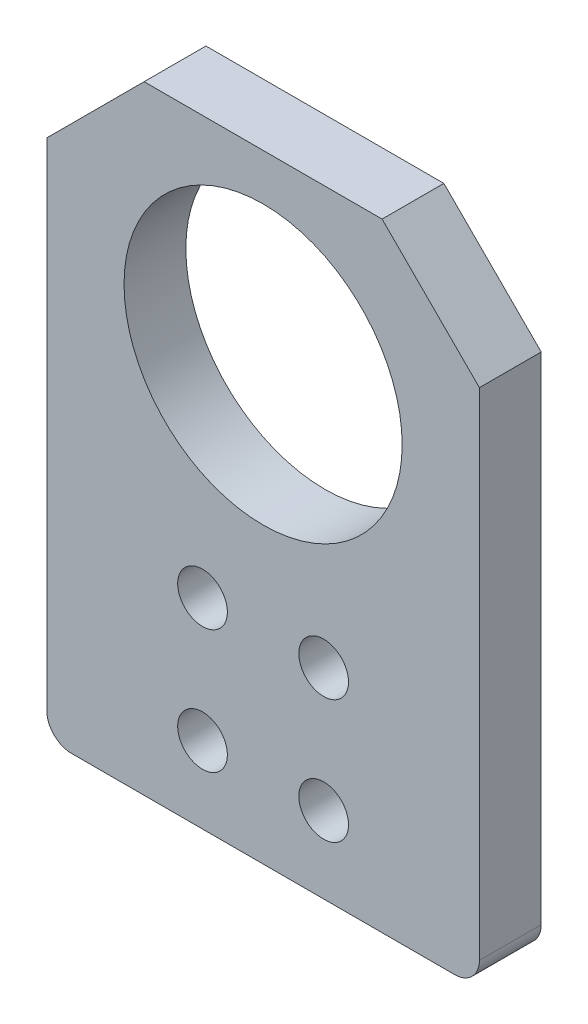
SolidWorks part; units mm, degrees
ref_plane "Front Plane" through (0, 0, 0) normal (0, 0, 1) x (1, 0, 0)
ref_plane "Top Plane" through (0, 0, 0) normal (0, 1, 0) x (1, 0, 0)
ref_plane "Right Plane" through (0, 0, 0) normal (1, 0, 0) x (0, 0, -1)
sketch "Sketch1" plane through (0, 0, 0) normal (0, 0, 1) x (1, 0, 0)
  line L1 (-22.225, -31.75) -> (22.225, -31.75)
  line L2 (-22.225, -31.75) -> (-22.225, 31.75)
  line L3 (-22.225, 31.75) -> (22.225, 31.75)
  line L4 (22.225, -31.75) -> (22.225, 31.75)
  line L5 (-22.225, -31.75) -> (22.225, 31.75) construction
  line L6 (-22.225, 31.75) -> (22.225, -31.75) construction
  point P0 (0, 0)
  dimension "D1" = 44.45
  dimension "D2" = 63.5
extrude "Boss-Extrude1" add sketch "Sketch1" along normal mid plane 6.35
chamfer "Chamfer1" distance 10 angle 45 2 edges at (22.225, 31.75, 0) (-22.225, 31.75, 0)
sketch "Sketch2" plane through (0, 0, 3.175) normal (0, 0, 1) x (1, 0, 0)
  line L0 (12.225, 31.75) -> (-12.225, 31.75) construction
  circle A0 centre (0, 12.7) radius 14.2875
  point P2 (0, 0)
  dimension "D1" = 28.575
  dimension "D2" = 19.05
extrude "Cut-Extrude1" cut sketch "Sketch2" against normal through all
hole_wizard "Tap Drill for #10-24 Tap1" positions "Sketch4" profile "Sketch5" hole size "#10-24" standard "ANSI Inch"
sketch "Sketch4" plane through (0, -31.75, 0) normal (0, -1, 0) x (-1, 0, 0)
  line L0 (15.875, 0) -> (-15.875, 0) construction
  point P0 (15.875, 0)
  point P2 (-15.875, 0)
  point P12 (-6.9325, 0)
  point P13 (0, 0)
  dimension "D1" = 31.75
sketch "Sketch5" plane through (-15.875, -31.75, 0) normal (1, 0, 0) x (0, 0, -1)
  line L0 (0, 0) -> (0, 20.1908)
  line L1 (0, 20.1908) -> (1.8986, 19.05)
  line L2 (1.8986, 19.05) -> (1.8986, 0)
  line L5 (1.8986, 0) -> (0, 0)
  line L10 (0, 20.1908) -> (-1.8987, 19.05) construction
  line L11 (0, -6.35) -> (0, 107.95) construction
  dimension "Hole Dia." = 3.7973
  dimension "Hole Depth" = 19.05
  dimension "Drill Angle" = 118
sketch "Sketch6" plane through (0, 0, 3.175) normal (0, 0, 1) x (1, 0, 0)
  line L0 (-22.225, -31.75) -> (22.225, -31.75) construction
  line L1 (-6.223, -23.876) -> (6.223, -23.876) construction
  line L2 (-6.223, -23.876) -> (-6.223, -11.176) construction
  line L3 (-6.223, -11.176) -> (6.223, -11.176) construction
  line L4 (6.223, -23.876) -> (6.223, -11.176) construction
  line L5 (-6.223, -23.876) -> (6.223, -11.176) construction
  line L6 (-6.223, -11.176) -> (6.223, -23.876) construction
  point P0 (0, -17.526)
  point P5 (0, 0)
  dimension "D1" = 7.874
  dimension "D2" = 12.446
  dimension "D3" = 12.7
hole_wizard "#10 Clearance Hole1" positions "Sketch7" profile "Sketch8" hole size "#10" standard "ANSI Inch"
sketch "Sketch7" plane through (0, 0, 3.175) normal (0, 0, 1) x (1, 0, 0)
  point P0 (-6.223, -11.176)
  point P3 (6.223, -11.176)
  point P6 (6.223, -23.876)
  point P9 (-6.223, -23.876)
sketch "Sketch8" plane through (-6.223, -11.176, 3.175) normal (1, 0, 0) x (0, -1, 0)
  line L0 (0, 0) -> (0, 14.2338)
  line L1 (0, 14.2338) -> (2.5527, 12.7)
  line L2 (2.5527, 12.7) -> (2.5527, 0)
  line L5 (2.5527, 0) -> (0, 0)
  line L10 (0, 14.2338) -> (-2.5527, 12.7) construction
  line L11 (0, -6.35) -> (0, 107.95) construction
  dimension "Hole Dia." = 5.1054
  dimension "Hole Depth" = 12.7
  dimension "Drill Angle" = 118
fillet "Fillet1" radius 2.54 2 edges at (22.225, -31.75, 0) (-22.225, -31.75, 0)
